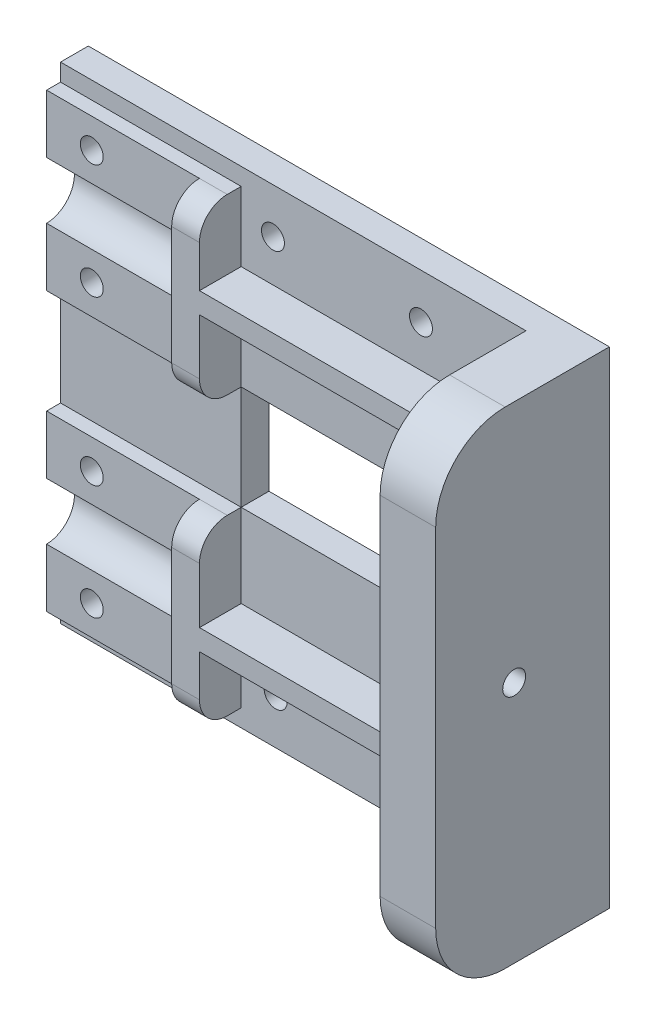
SolidWorks part; units mm, degrees
ref_plane "Front Plane" through (0, 0, 0) normal (0, 0, 1) x (1, 0, 0)
ref_plane "Top Plane" through (0, 0, 0) normal (0, 1, 0) x (1, 0, 0)
ref_plane "Right Plane" through (0, 0, 0) normal (1, 0, 0) x (0, 0, -1)
sketch "Sketch1" plane through (0, 0, 0) normal (0, 0, 1) x (1, 0, 0)
  line L1 (-37.5, 35) -> (37.5, 35)
  line L2 (-37.5, 35) -> (-37.5, -35)
  line L3 (-37.5, -35) -> (37.5, -35)
  line L4 (37.5, 35) -> (37.5, -35)
  line L5 (-37.5, 35) -> (37.5, -35) construction
  line L6 (-37.5, -35) -> (37.5, 35) construction
  point P0 (0, 0)
  dimension "D1" = 70
  dimension "D2" = 75
extrude "Boss-Extrude1" add sketch "Sketch1" along normal blind 4
sketch "Sketch4" plane through (0, 0, 4) normal (0, 0, 1) x (1, 0, 0)
  line L0 (-37.5, 35) -> (-37.5, -35) construction
  line L1 (-37.5, 7.5) -> (-11.5, 7.5)
  line L2 (-37.5, 7.5) -> (-37.5, 32.5)
  line L3 (-37.5, 32.5) -> (-11.5, 32.5)
  line L4 (-11.5, 7.5) -> (-11.5, 32.5)
  line L5 (-37.5, -20) -> (-25.496, -20) construction
  line L6 (-37.5, -7.5) -> (-11.5, -7.5)
  line L7 (-37.5, -7.5) -> (-37.5, -32.5)
  line L8 (-37.5, -32.5) -> (-11.5, -32.5)
  line L9 (-11.5, -7.5) -> (-11.5, -32.5)
  line L10 (-25.496, -20) -> (-25.496, 20) construction
  line L11 (-25.496, 20) -> (-37.5, 20) construction
  line L12 (-25.496, 0) -> (0, 0) construction
  dimension "D1" = 40
  dimension "D2" = 25
  dimension "D3" = 26
extrude "Boss-Extrude2" add sketch "Sketch4" along normal blind 2
sketch "Sketch3" plane through (-37.5, 0, 0) normal (-1, 0, 0) x (0, 0, 1)
  line L0 (2, 20) -> (2, -20) construction
  line L3 (2, 20) -> (6.1, 20) construction
  line L5 (6, 32.5) -> (6, 7.5) construction
  line L6 (2, -20) -> (6.1, -20) construction
  line L7 (2, 0) -> (0, 0) construction
  line L8 (4, 35) -> (4, 32.5) construction
  circle A0 centre (6.1, 20) radius 4.1
  circle A1 centre (6.1, -20) radius 4.1
  point P13 (6, 20)
  dimension "D1" = 8.2
  dimension "D3" = 2
extrude "Cut-Extrude1" cut sketch "Sketch3" against normal blind 22
sketch "Sketch5" plane through (0, 0, 4) normal (0, 0, 1) x (1, 0, 0)
  line L0 (37.5, -35) -> (37.5, 35) construction
  line L1 (37.5, -22.5) -> (77.5, -22.5)
  line L2 (37.5, -22.5) -> (37.5, 22.5)
  line L3 (37.5, 22.5) -> (77.5, 22.5)
  line L4 (77.5, -22.5) -> (77.5, 22.5)
  line L5 (77.5, 0) -> (0, 0) construction
  dimension "D1" = 40
  dimension "D2" = 45
extrude "Boss-Extrude3" add sketch "Sketch5" against normal up to surface (4 mm away) up to face at (0, 0, 0)
sketch "Sketch7" plane through (0, 0, 0) normal (0, 0, -1) x (-1, 0, 0)
  line L0 (-39, -15.5) -> (-70, -15.5) construction
  line L1 (-54.5, 0) -> (-77.5, 0) construction
  line L2 (-77.5, 22.5) -> (-77.5, -22.5) construction
  circle B0 centre (-54.5, 0) radius 11.3
  circle B1 centre (-70, 15.5) radius 1.5
  circle B2 centre (-39, 15.5) radius 1.5
  circle B3 centre (-39, -15.5) radius 1.5
  circle B4 centre (-70, -15.5) radius 1.5
  dimension "D1" = 23
sketch_block_instance "Block1-1"
sketch_block "Block1"
extrude "Cut-Extrude2" cut sketch "Sketch7" against normal through all
sketch "Sketch8" plane through (0, 0, 6) normal (0, 0, 1) x (1, 0, 0)
  line L0 (-11.5, 32.5) -> (-37.5, 32.5) construction
  line L1 (-11.5, 7.5) -> (-15.5, 7.5)
  line L2 (-11.5, 7.5) -> (-11.5, 32.5)
  line L3 (-11.5, 32.5) -> (-15.5, 32.5)
  line L4 (-15.5, 7.5) -> (-15.5, 32.5)
  line L5 (-11.5, -7.5) -> (-37.5, -7.5) construction
  line L6 (-11.5, -32.5) -> (-15.5, -32.5)
  line L7 (-11.5, -32.5) -> (-11.5, -7.5)
  line L8 (-11.5, -7.5) -> (-15.5, -7.5)
  line L9 (-15.5, -32.5) -> (-15.5, -7.5)
extrude "Boss-Extrude4" add sketch "Sketch8" along normal blind 4
fillet "Fillet2" radius 4 4 edges at (-13.5, -32.5, 10) (-13.5, -7.5, 10) (-13.5, 32.5, 10) (-13.5, 7.5, 10)
sketch "Sketch10" plane through (0, 0, 4) normal (0, 0, 1) x (1, 0, 0)
  line L0 (-11.5, 7.5) -> (-11.5, 32.5) construction
  line L1 (77.5, 22.5) -> (-11.5, 22.5)
  line L2 (77.5, 22.5) -> (77.5, 19.5)
  line L3 (77.5, 19.5) -> (-11.5, 19.5)
  line L4 (-11.5, 22.5) -> (-11.5, 19.5)
  line L5 (-11.5, -32.5) -> (-11.5, -7.5) construction
  line L6 (77.5, -22.5) -> (-11.5, -22.5)
  line L7 (77.5, -22.5) -> (77.5, -19.5)
  line L8 (77.5, -19.5) -> (-11.5, -19.5)
  line L9 (-11.5, -22.5) -> (-11.5, -19.5)
  dimension "D1" = 3
extrude "Boss-Extrude5" add sketch "Sketch10" along normal up to surface (6 mm away) up to face at (-13.5, -20, 10)
chamfer "Chamfer2" distance 4 angle 45 4 edges at (77.5, 22.5, 5) (77.5, -22.5, 5)
fillet "Fillet3" radius 1 2 edges at (76.5, 19.5, 7) (76.5, -19.5, 7)
sketch "Sketch11" plane through (0, 0, 0) normal (0, 0, -1) x (-1, 0, 0)
  line L0 (-37.5, 26.5) -> (-37.5, -26.5)
  line L1 (-37.5, 26.5) -> (-77.5, 26.5)
  line L2 (-37.5, -26.5) -> (-77.5, -26.5)
  line L3 (-77.5, 26.5) -> (-77.5, -26.5)
  line L4 (-77.5, 18.5) -> (-77.5, -18.5) construction
extrude "Cut-Extrude3" cut sketch "Sketch11" against normal through all
sketch "Sketch13" plane through (37.5, 0, 0) normal (1, 0, 0) x (0, 0, -1)
  line L1 (0, 35) -> (-25, 35)
  line L2 (0, 35) -> (0, -35)
  line L3 (0, -35) -> (-25, -35)
  line L4 (-25, 35) -> (-25, -35)
  dimension "D1" = 25
extrude "Boss-Extrude6" add sketch "Sketch13" against normal blind 8
sketch "Sketch14" plane through (0, 0, 4) normal (0, 0, 1) x (1, 0, 0)
  line L0 (-37.5, 7.5) -> (-15.5, 7.5) construction
  line L1 (-11.5, 7.5) -> (29.5, 7.5)
  line L2 (-11.5, 7.5) -> (-11.5, -7.5)
  line L3 (-11.5, -7.5) -> (29.5, -7.5)
  line L4 (29.5, 7.5) -> (29.5, -7.5)
  line L5 (29.5, 19.5) -> (29.5, -19.5) construction
  line L6 (-11.5, -7.5) -> (-37.5, -7.5) construction
  line L7 (-11.5, 7.5) -> (-11.5, 19.5) construction
extrude "Cut-Extrude4" cut sketch "Sketch14" against normal through all
fillet "Fillet4" radius 10 2 edges at (33.5, 35, 25) (33.5, -35, 25)
sketch "Sketch15" plane through (37.5, 0, 0) normal (1, 0, 0) x (0, 0, -1)
  circle A1 centre (-13.7, 0) radius 1.65
  circle A2 centre (-13.7, 0) radius 1.65
  dimension "D1" = 0
extrude "Cut-Extrude5" cut sketch "Sketch15" against normal blind 10
sketch "Sketch16" plane through (0, 0, 0) normal (0, 0, -1) x (-1, 0, 0)
  circle A1 centre (31, 28.2381) radius 1.65
  circle A2 centre (31, 28.2381) radius 1.65
  circle A3 centre (31, 11.7619) radius 1.65
  circle A4 centre (31, 11.7619) radius 1.65
  circle A5 centre (31, -11.7619) radius 1.65
  circle A6 centre (31, -11.7619) radius 1.65
  circle A7 centre (31, -28.2381) radius 1.65
  circle A8 centre (31, -28.2381) radius 1.65
  circle A9 centre (-14.382, 28.5) radius 1.65
  circle A10 centre (-14.382, 28.5) radius 1.65
  circle A11 centre (6.922, 28.5) radius 1.65
  circle A12 centre (6.922, 28.5) radius 1.65
  circle A13 centre (-13.997, -28.5) radius 1.65
  circle A14 centre (-13.997, -28.5) radius 1.65
  circle A15 centre (6.537, -28.5) radius 1.65
  circle A16 centre (6.537, -28.5) radius 1.65
  dimension "D1" = 0
  dimension "D2" = 0
  dimension "D3" = 0
  dimension "D4" = 0
  dimension "D5" = 0
  dimension "D6" = 0
  dimension "D7" = 0
  dimension "D8" = 0
extrude "Cut-Extrude6" cut sketch "Sketch16" against normal through all both and the other way through all
